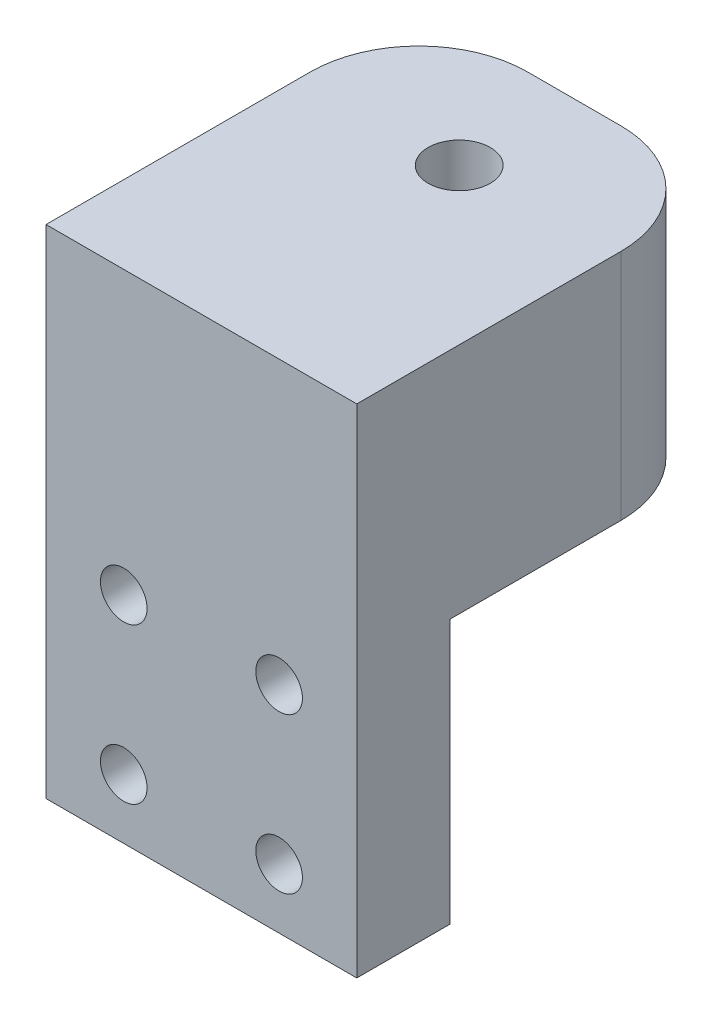
SolidWorks part; units mm, degrees
ref_plane "Спереди" through (0, 0, 0) normal (0, 0, 1) x (1, 0, 0)
ref_plane "Сверху" through (0, 0, 0) normal (0, 1, 0) x (1, 0, 0)
ref_plane "Справа" through (0, 0, 0) normal (1, 0, 0) x (0, 0, -1)
sketch "Эскиз1" plane through (0, 0, 0) normal (0, 0, 1) x (1, 0, 0)
  line L1 (-10, -10) -> (10, -10)
  line L2 (-10, -10) -> (-10, 10)
  line L3 (-10, 10) -> (10, 10)
  line L4 (10, -10) -> (10, 10)
  line L5 (-10, -10) -> (10, 10) construction
  line L6 (-10, 10) -> (10, -10) construction
  line L7 (-5, -6.152) -> (5, -6.152)
  line L8 (-5, -6.152) -> (-5, 3.848)
  line L9 (-5, 3.848) -> (5, 3.848)
  line L10 (5, -6.152) -> (5, 3.848)
  line L11 (-5, -6.152) -> (5, 3.848) construction
  line L12 (-5, 3.848) -> (5, -6.152) construction
  circle A0 centre (-5, -6.152) radius 1.5
  circle A1 centre (-5, 3.848) radius 1.5
  circle A2 centre (5, 3.848) radius 1.5
  circle A3 centre (5, -6.152) radius 1.5
  point P0 (0, 0)
  point P6 (0, -1.152)
  dimension "D5" = 3
  dimension "D6" = 3
  dimension "D7" = 3
  dimension "D8" = 3
  dimension "D1" = 20
  dimension "D2" = 20
  dimension "D3" = 10
  dimension "D4" = 10
extrude "Бобышка-Вытянуть1" add sketch "Эскиз1" along normal blind 6 contours L1 L4 L3 L2 A3 L7 A0 L8 A1 L9 A2 L10 | A3 L10 A2 L9 A1 L8 A0 L7
sketch "Эскиз2" plane through (0, 0, 0) normal (0, 0, -1) x (-1, 0, 0)
  line L0 (10, -10) -> (10, 10) construction
  line L1 (-10, 10) -> (10, 10)
  line L2 (-10, 10) -> (-10, 7)
  line L3 (-10, 7) -> (10, 7)
  line L4 (10, 10) -> (10, 7)
  dimension "D1" = 3
extrude "Бобышка-Вытянуть2" add sketch "Эскиз2" along normal blind 18
sketch "Эскиз3" plane through (0, 10, 0) normal (0, 1, 0) x (1, 0, 0)
  line L1 (-10, 18) -> (10, 18)
  line L2 (-10, 18) -> (-10, -6)
  line L3 (-10, -6) -> (10, -6)
  line L4 (10, 18) -> (10, -6)
extrude "Бобышка-Вытянуть3" add sketch "Эскиз3" along normal blind 12
sketch "Эскиз4" plane through (0, 22, 0) normal (0, 1, 0) x (1, 0, 0)
  line L0 (-10, 2.5) -> (10, 2.5)
  line L1 (-3, 18) -> (3, 18)
  line L2 (-10, 11) -> (-10, -6)
  line L3 (-10, -6) -> (10, -6)
  line L4 (10, 11) -> (10, -6)
  line L5 (0, 18) -> (0, -6)
  line L7 (-10, 18) -> (10, 18)
  line L8 (-10, 18) -> (-10, -6)
  line L9 (-10, -6) -> (10, -6)
  line L10 (10, 18) -> (10, -6)
  arc A0 (10, 11) -> (3, 18) centre (3, 11) ccw
  arc A1 (-10, 11) -> (-3, 18) centre (-3, 11) cw
  circle A2 centre (0, 10.591) radius 2
  point P12 (-10, 18)
  line M8 (-10, 18) -> (-10, -6)
  line M10 (10, -6) -> (10, 18)
  line M11 (10, 18) -> (-10, 18)
  dimension "D1" = 7
  dimension "D2" = 4
extrude "Вырез-Вытянуть1" cut sketch "Эскиз4" against normal through all contours A1 M8 M11 | L5 A2 | L5 A2 | A0 M10 M11
